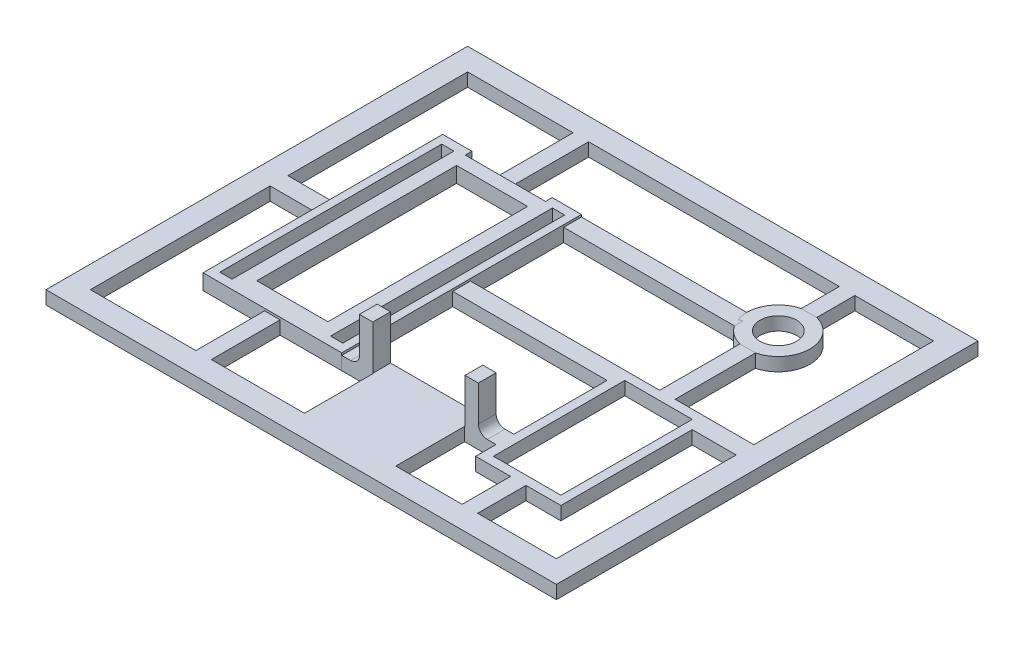
SolidWorks part; units mm, degrees
ref_plane "Front Plane" through (0, 0, 0) normal (0, 0, 1) x (1, 0, 0)
ref_plane "Top Plane" through (0, 0, 0) normal (0, 1, 0) x (1, 0, 0)
ref_plane "Right Plane" through (0, 0, 0) normal (1, 0, 0) x (0, 0, -1)
sketch "Sketch2" plane through (0, 0, 0) normal (0, 1, 0) x (1, 0, 0)
  line L4 (15.625, -27) -> (15.625, 27)
  line L5 (-14.125, 25.5) -> (-12.325, 25.5) construction
  line L7 (-14.125, -25.5) -> (14.125, -25.5)
  line L8 (-15.625, 27) -> (15.625, 27)
  line L20 (-14.125, -25.5) -> (-14.125, 25.5)
  line L37 (-14.125, 25.5) -> (14.125, 25.5)
  line L38 (14.125, -25.5) -> (14.125, 25.5)
  line L39 (-14.125, -25.5) -> (14.125, 25.5) construction
  line L40 (-14.125, 25.5) -> (14.125, -25.5) construction
  line L41 (-9.05, 25.5) -> (9.05, 25.5)
  line L42 (-9.05, 25.5) -> (-9.05, 31.25)
  line L43 (-9.05, 31.25) -> (9.05, 31.25)
  line L44 (9.05, 25.5) -> (9.05, 31.25)
  line L45 (0, -55) -> (0, 55) construction
  line L46 (-13.85, 25.0035) -> (-11.1, 25.0035)
  line L47 (-13.85, 25.0035) -> (-13.85, -24.9965)
  line L48 (-13.85, -24.9965) -> (-11.1, -24.9965)
  line L49 (-11.1, 25.0035) -> (-11.1, -24.9965)
  line L50 (13.85, -24.9965) -> (11.1, -24.9965)
  line L51 (11.1, 25.0035) -> (11.1, -24.9965)
  line L52 (13.85, 25.0035) -> (13.85, -24.9965)
  line L53 (13.85, 25.0035) -> (11.1, 25.0035)
  line L54 (-15.625, -27) -> (-15.625, 27)
  line L55 (-8, 22.5) -> (8, 22.5)
  line L56 (-8, 22.5) -> (-8, -22.5)
  line L57 (-8, -22.5) -> (8, -22.5)
  line L58 (8, 22.5) -> (8, -22.5)
  line L59 (-15.625, -27) -> (15.625, -27)
  point P0 (0, 0)
  point P9 (0, 31.25)
  point P10 (0, 25.5)
  point P14 (0, 22.5)
  point P17 (-12.475, 25.0035)
  point P18 (-12.475, -24.9965)
  point P29 (0, 0)
  point P30 (-8, 0)
  dimension "D3" = 18.1
  dimension "D8" = 1.65
  dimension "D1" = 28.25
  dimension "D2" = 51
  dimension "D4" = 5.75
  dimension "D5" = 1.8
  dimension "D6" = 2.75
  dimension "D7" = 50
  dimension "D11" = 1.5
  dimension "D9" = 16
  dimension "D10" = 45
extrude "Boss-Extrude1" add sketch "Sketch2" along normal blind 3.5 separate body
sketch "Sketch3" plane through (0, 0, 0) normal (0, 1, 0) x (1, 0, 0)
  line L0 (50.4, 2) -> (69.6, 2)
  line L1 (51.4, -30.6) -> (68.6, -30.6) construction
  line L2 (51.4, -30.6) -> (51.4, 1) construction
  line L3 (51.4, 1) -> (68.6, 1) construction
  line L4 (68.6, -30.6) -> (68.6, 1) construction
  line L5 (51.4, -30.6) -> (68.6, 1) construction
  line L6 (51.4, 1) -> (68.6, -30.6) construction
  line L7 (69.6, -31.6) -> (69.6, 2)
  line L8 (50.4, -31.6) -> (69.6, -31.6)
  line L9 (50.4, -31.6) -> (50.4, 2)
  line L10 (52.4, 0) -> (67.6, 0)
  line L11 (67.6, -29.6) -> (67.6, 0)
  line L12 (52.4, -29.6) -> (67.6, -29.6)
  line L13 (52.4, -29.6) -> (52.4, 0)
  line L15 (8, 22.5) -> (8, -22.5) construction
  line L16 (0, 0) -> (8, 0) construction
  point P0 (60, -14.8)
  dimension "D1" = 31.6
  dimension "D2" = 17.2
  dimension "D5" = 60
  dimension "D3" = 1
  dimension "D4" = 1
extrude "Boss-Extrude3" add sketch "Sketch3" along normal blind 3 separate body
sketch "Sketch5" plane through (0, 0, 0) normal (0, 1, 0) x (1, 0, 0)
  line L0 (67.6, 0) -> (52.4, 0) construction
  circle A0 centre (60, 27) radius 4.125
  circle A1 centre (60, 27) radius 7.125
  point P4 (60, 0)
  point P5 (42.5, 28.5324)
  point P7 (0, 0)
  point P10 (0, 0)
  dimension "D1" = 8.25
  dimension "D2" = 3
extrude "Boss-Extrude5" add sketch "Sketch5" along normal blind 3 separate body
sketch "Sketch4" plane through (0, 0, 0) normal (0, 1, 0) x (1, 0, 0)
  line L0 (69.6, 2) -> (50.4, 2) construction
  line L1 (-28.0125, 45) -> (81.9875, 45)
  line L2 (-28.0125, 45) -> (-28.0125, -45)
  line L3 (-28.0125, -45) -> (81.9875, -45)
  line L4 (81.9875, 45) -> (81.9875, -45)
  line L5 (-25.5125, 42.5) -> (79.4875, 42.5)
  line L6 (79.4875, 42.5) -> (79.4875, -42.5)
  line L7 (-25.5125, -42.5) -> (79.4875, -42.5)
  line L8 (-25.5125, 42.5) -> (-25.5125, -42.5)
  line L9 (-9.05, 25.5) -> (9.05, 25.5) construction
  line L14 (50.4, 2) -> (50.4, -31.6) construction
  line L19 (69.6, -31.6) -> (69.6, 2) construction
  line L20 (69.6, 2) -> (79.4875, 2)
  line L21 (69.6, 2) -> (69.6, -2)
  line L22 (69.6, -2) -> (79.4875, -2)
  line L23 (79.4875, 2) -> (79.4875, -2)
  line L24 (-15.625, -27) -> (-15.625, 27) construction
  line L25 (-15.625, 2) -> (-25.5125, 2)
  line L26 (-15.625, 2) -> (-15.625, -2)
  line L27 (-15.625, -2) -> (-25.5125, -2)
  line L28 (-25.5125, 2) -> (-25.5125, -2)
  line L29 (15.625, -27) -> (50.4, -27)
  line L32 (58.25, 42.5) -> (61.75, 42.5)
  line L33 (58.25, 42.5) -> (58.25, 33.9067)
  line L34 (15.625, -27) -> (15.625, 27) construction
  line L35 (15.625, 2) -> (50.4, 2)
  line L36 (15.625, 2) -> (15.625, -2)
  line L37 (15.625, -2) -> (50.4, -2)
  line L38 (50.4, 2) -> (50.4, -2)
  line L39 (50.4, 2) -> (50.4, -31.6) construction
  line L41 (58.25, 33.9067) -> (61.75, 33.9067)
  line L42 (-30.5125, 47.5) -> (-30.5125, -47.5)
  line L43 (-30.5125, -47.5) -> (84.4875, -47.5)
  line L44 (84.4875, 47.5) -> (84.4875, -47.5)
  line L45 (-30.5125, 47.5) -> (84.4875, 47.5)
  line L46 (61.75, 42.5) -> (61.75, 33.9067)
  line L47 (-1.75, 42.5) -> (1.75, 42.5)
  line L48 (-1.75, 42.5) -> (-1.75, 25.5)
  line L49 (-1.75, 25.5) -> (1.75, 25.5)
  line L50 (1.75, 42.5) -> (1.75, 25.5)
  line L52 (-15.625, -27) -> (15.625, -27) construction
  line L53 (-1.75, -27) -> (1.75, -27)
  line L54 (-1.75, -27) -> (-1.75, -42.5)
  line L55 (-1.75, -42.5) -> (1.75, -42.5)
  line L56 (1.75, -27) -> (1.75, -42.5)
  line L57 (58.25, 20.0933) -> (61.75, 20.0933)
  line L58 (58.25, 20.0933) -> (58.25, 2)
  line L59 (58.25, 2) -> (61.75, 2)
  line L60 (61.75, 20.0933) -> (61.75, 2)
  line L61 (50.4, -31.6) -> (69.6, -31.6) construction
  line L62 (58.25, -31.6) -> (61.75, -31.6)
  line L63 (58.25, -31.6) -> (58.25, -42.5)
  line L64 (58.25, -42.5) -> (61.75, -42.5)
  line L65 (61.75, -31.6) -> (61.75, -42.5)
  line L66 (67.6, 0) -> (52.4, 0) construction
  line L67 (52.4, -29.6) -> (67.6, -29.6) construction
  line L68 (15.625, -27) -> (15.625, -23)
  line L69 (15.625, -23) -> (50.4, -23)
  line L70 (50.4, -27) -> (50.4, -23)
  line L72 (15.625, 27) -> (54.1038, 27)
  line L73 (15.625, 27) -> (15.625, 23)
  line L74 (15.625, 23) -> (54.1038, 23)
  line L75 (54.1038, 27) -> (54.1038, 23)
  line L76 (22.7125, -27) -> (43.3125, -27)
  line L77 (22.7125, -27) -> (22.7125, -42.5)
  line L78 (22.7125, -42.5) -> (43.3125, -42.5)
  line L79 (43.3125, -27) -> (43.3125, -42.5)
  circle A0 centre (60, 27) radius 7.125 construction
  circle A1 centre (60, 27) radius 7.125 construction
  point P4 (-28.0125, 0)
  point P9 (0, -27)
  point P51 (60, 33.9067)
  point P52 (60, 2)
  point P69 (60, 0)
  point P72 (60, -29.6)
  point P73 (60, -31.6)
  point P74 (0, 25.5)
  point P75 (-15.625, 0)
  point P76 (15.625, 0)
  point P77 (69.6, 0)
  point P90 (33.0125, -27)
  point P91 (33.0125, -23)
  dimension "D2" = 90
  dimension "D4" = 3.5
  dimension "D5" = 4
  dimension "D6" = 3.5
  dimension "D7" = 4
  dimension "D8" = 4
  dimension "D10" = 3.5
  dimension "D11" = 115
  dimension "D12" = 20.6
  dimension "D3" = 2.5
  dimension "D9" = 2.5
extrude "Boss-Extrude4" add sketch "Sketch4" along normal blind 3
sketch "Sketch7" plane through (0, 3, 0) normal (0, 1, 0) x (1, 0, 0)
  line L0 (15.625, -23) -> (50.4, -23) construction
  line L1 (22.6125, -23) -> (43.4125, -23) construction
  line L2 (22.6125, -23) -> (22.6125, -27) construction
  line L3 (22.6125, -27) -> (43.4125, -27) construction
  line L4 (43.4125, -23) -> (43.4125, -27) construction
  line L5 (15.625, -27) -> (22.7125, -27) construction
  line L7 (22.6125, -23) -> (19.6125, -23)
  line L8 (22.6125, -23) -> (22.6125, -27)
  line L9 (22.6125, -27) -> (19.6125, -27)
  line L10 (19.6125, -23) -> (19.6125, -27)
  line L11 (43.4125, -23) -> (46.4125, -23)
  line L12 (43.4125, -23) -> (43.4125, -27)
  line L13 (43.4125, -27) -> (46.4125, -27)
  line L14 (46.4125, -23) -> (46.4125, -27)
  point P8 (33.0125, -23)
  point P9 (33.0125, -23)
  dimension "D1" = 20.8
  dimension "D2" = 3
extrude "Boss-Extrude6" add sketch "Sketch7" along normal blind 10
fillet "Fillet1" radius 2 1 edges at (19.6125, 3, 25)
fillet "Fillet2" radius 2 1 edges at (46.4125, 3, 25)
